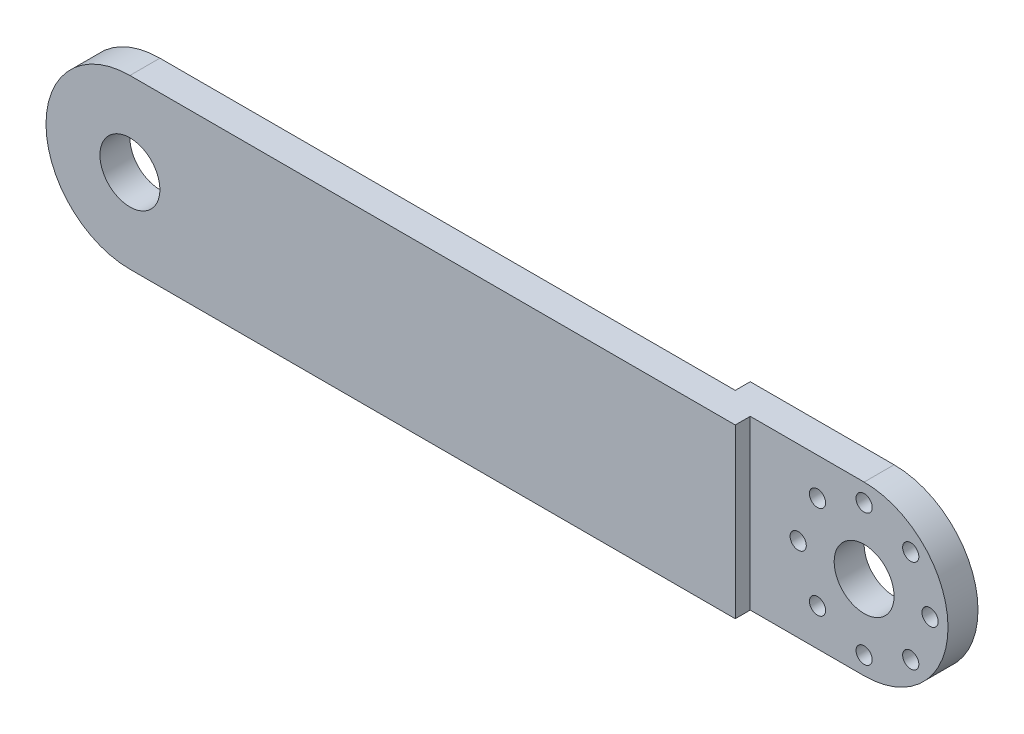
SolidWorks part; units mm, degrees
ref_plane "Plano frontal" through (0, 0, 0) normal (0, 0, 1) x (1, 0, 0)
ref_plane "Plano superior" through (0, 0, 0) normal (0, 1, 0) x (1, 0, 0)
ref_plane "Plano direito" through (0, 0, 0) normal (1, 0, 0) x (0, 0, -1)
sketch "Esboço1" plane through (0, 0, 0) normal (0, 0, 1) x (1, 0, 0)
  line L0 (0, -14) -> (122, -14)
  line L1 (0, 14) -> (122, 14)
  arc A0 (0, 14) -> (0, -14) centre (0, 0) ccw
  arc A1 (122, -14) -> (122, 14) centre (122, 0) ccw
  dimension "D1" = 28
  dimension "D2" = 28
  dimension "D3" = 122
extrude "Ressalto-extrusão1" add sketch "Esboço1" along normal blind 5
sketch "Esboço2" plane through (0, 0, 0) normal (0, 0, -1) x (-1, 0, 0)
  circle A1 centre (-125.3271, 10.4848) radius 1.35
  circle A2 centre (-116.9388, 9.7665) radius 1.35
  circle A3 centre (-111.5152, 3.3271) radius 1.35
  circle A4 centre (-112.2335, -5.0612) radius 1.35
  circle A5 centre (-118.6729, -10.4848) radius 1.3731
  circle A6 centre (-127.0612, -9.7665) radius 1.3301
  circle A7 centre (-132.4848, -3.3271) radius 1.35
  circle A8 centre (-131.7665, 5.0612) radius 1.35
  circle A9 centre (-122, 0) radius 5
extrude "Corte-extrusão1" cut sketch "Esboço2" against normal through all
sketch "Esboço3" plane through (0, 0, 0) normal (0, 0, -1) x (-1, 0, 0)
  circle A0 centre (0, 0) radius 5
extrude "Corte-extrusão2" cut sketch "Esboço3" against normal through all
sketch "Esboço5" plane through (0, 0, 0) normal (0, 0, -1) x (-1, 0, 0)
  line L0 (-106, 14) -> (-137.2412, 14)
  line L1 (-106, 14) -> (-106, -14)
  line L2 (-122, 14) -> (0, 14) construction
  line L3 (0, -14) -> (-122, -14) construction
  line L4 (-137.2412, 14) -> (-137.2412, -14)
  line L5 (-137.2412, -14) -> (-106, -14)
extrude "Corte-extrusão3" cut sketch "Esboço5" against normal through all
sketch "Esboço6" plane through (0, 0, 0) normal (0, 0, -1) x (-1, 0, 0)
  line L0 (-106, 14) -> (-101, 14)
  line L1 (-106, 14) -> (0, 14) construction
  line L2 (-101, 14) -> (-101, -14)
  line L3 (0, -14) -> (-106, -14) construction
  line L4 (-101, -14) -> (-106, -14)
  line L5 (-106, -14) -> (-106, 14)
extrude "Ressalto-extrusão2" add sketch "Esboço6" along normal blind 2.5
sketch "Esboço7" plane through (0, 0, -2.5) normal (0, 0, -1) x (-1, 0, 0)
  line L0 (-106, 14) -> (-120, 14)
  line L1 (-106, 14) -> (-106, -14) construction
  line L2 (-106, -14) -> (-120, -14)
  line L8 (-106, 14) -> (-106, -14)
  line L9 (-106, -14) -> (-101, -14)
  line L10 (-101, -14) -> (-101, 14)
  line L11 (-101, 14) -> (-106, 14)
  line L12 (-106, 14) -> (-106, -14)
  arc A0 (-120, 14) -> (-120, -14) centre (-120, 0) ccw
  dimension "D1" = 14
  dimension "D2" = 14
  dimension "D3" = 0
extrude "Ressalto-extrusão4" add sketch "Esboço7" against normal blind 5
sketch "Esboço8" plane through (0, 0, -2.5) normal (0, 0, -1) x (-1, 0, 0)
  circle A1 centre (-120, 0) radius 5
  circle A2 centre (-120, 11) radius 1.35
  circle A3 centre (-109, 0) radius 1.35
  circle A4 centre (-120, -11) radius 1.35
  circle A5 centre (-131, 0) radius 1.35
  circle A6 centre (-112.2218, 7.7782) radius 1.35
  circle A7 centre (-112.2218, -7.7782) radius 1.35
  circle A8 centre (-127.7782, -7.7782) radius 1.35
  circle A9 centre (-127.7782, 7.7782) radius 1.35
  dimension "D1" = 2.7
  dimension "D2" = 2.7
  dimension "D3" = 11
  dimension "D4" = 11
  dimension "D5" = 11
  dimension "D6" = 11
extrude "Corte-extrusão4" cut sketch "Esboço8" against normal through all
sketch "Esboço10" plane through (0, -14, 0) normal (0, -1, 0) x (1, 0, 0)
  line L0 (106, 2.5) -> (101, 2.5)
  line L1 (101, 2.5) -> (101, 5)
  line L2 (0, 5) -> (106, 5) construction
  line L3 (101, 5) -> (106, 5)
  line L4 (106, 5) -> (106, 2.5)
  line L5 (101, 0) -> (96, 0)
  line L6 (0, 0) -> (101, 0) construction
  line L7 (101, 0) -> (101, -2.5)
  line L8 (101, -2.5) -> (96, -2.5)
  line L9 (96, -2.5) -> (96, 0)
extrude "Corte-extrusão5" cut sketch "Esboço10" against normal through all contours L1 L3 L4 L0
sketch "Esboço11" plane through (0, -14, 0) normal (0, -1, 0) x (1, 0, 0)
  line L4 (101, 0) -> (96, 0)
  line L5 (0, 0) -> (101, 0) construction
  line L6 (101, 0) -> (101, -2.5)
  line L7 (101, -2.5) -> (96, -2.5)
  line L8 (96, -2.5) -> (96, 0)
extrude "Ressalto-extrusão5" add sketch "Esboço11" against normal through all
